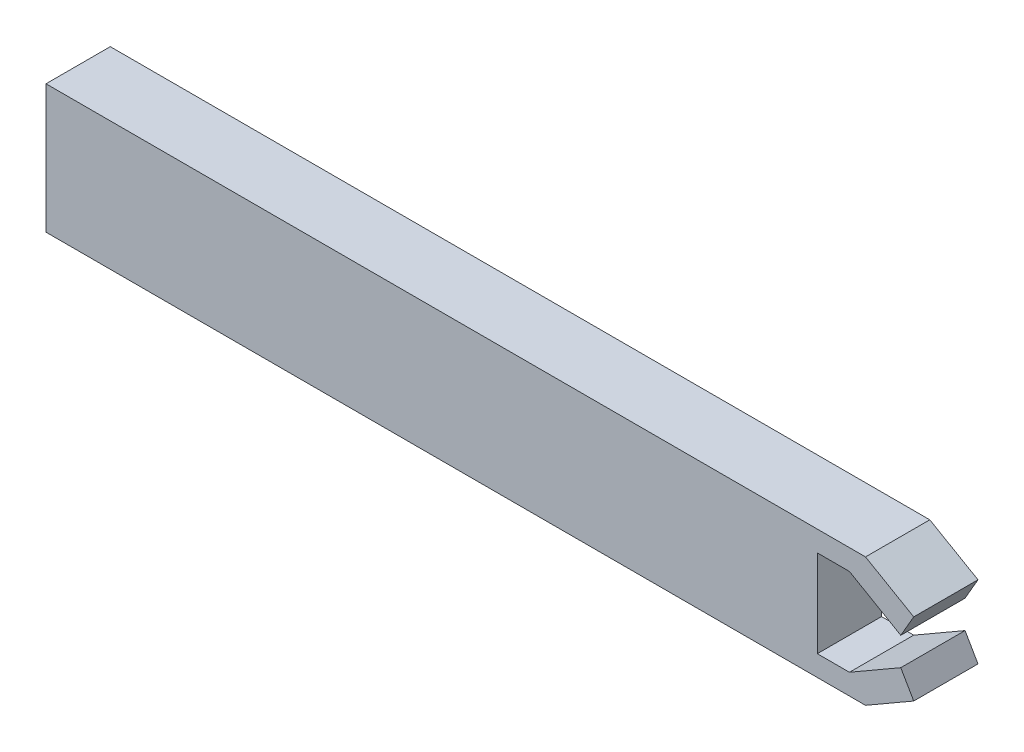
SolidWorks part; units mm, degrees
ref_plane "Front Plane" through (0, 0, 0) normal (0, 0, 1) x (1, 0, 0)
ref_plane "Top Plane" through (0, 0, 0) normal (0, 1, 0) x (1, 0, 0)
ref_plane "Right Plane" through (0, 0, 0) normal (1, 0, 0) x (0, 0, -1)
sketch "Sketch1" plane through (0, 0, 0) normal (0, 0, 1) x (1, 0, 0)
  line L0 (-15, 0) -> (-270, 0)
  line L1 (0, 8.6603) -> (0, 31.3397)
  line L2 (-270, 0) -> (-270, 40)
  line L3 (-15, 40) -> (-270, 40)
  line L5 (-15, 40) -> (0, 31.3397)
  line L7 (0, 31.3397) -> (-4.0288, 24.3616)
  line L8 (-20, 33.5826) -> (-4.0288, 24.3616)
  line L11 (-20, 33.5826) -> (-30, 33.5826)
  line L13 (0, 20) -> (-67.3672, 20) construction
  line L14 (-20, 6.4174) -> (-30, 6.4174)
  line L18 (0, 8.6603) -> (-4.0288, 15.6384)
  line L19 (-20, 6.4174) -> (-4.0288, 15.6384)
  line L21 (-15, 0) -> (0, 8.6603)
  line L22 (-30, 33.5826) -> (-30, 6.4174)
  point P1 (0, 0)
  point P5 (0, 0)
  dimension "D1" = 30
  dimension "D4" = 30
extrude "Boss-Extrude1" add sketch "Sketch1" along normal blind 20
